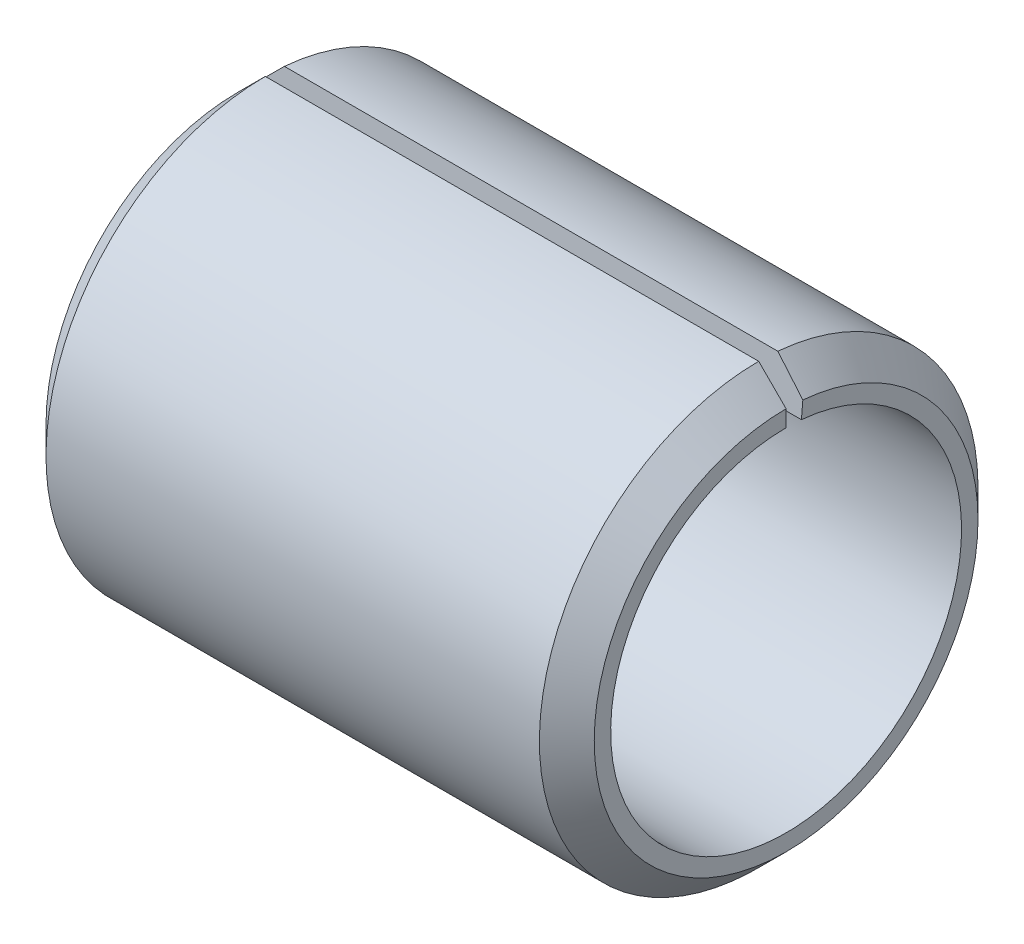
SolidWorks part; units mm, degrees
material "AISI 1020 Acier laminé à froid"
ref_plane "Plan de face" through (0, 0, 0) normal (0, 0, 1) x (1, 0, 0)
ref_plane "Plan de dessus" through (0, 0, 0) normal (0, 1, 0) x (1, 0, 0)
ref_plane "Plan de droite" through (0, 0, 0) normal (1, 0, 0) x (0, 0, -1)
sketch "Esquisse1" plane through (0, 0, 0) normal (0, 0, 1) x (1, 0, 0)
  line L0 (-5, 3.2) -> (-5, 4)
  line L1 (-5, 4) -> (5, 4)
  line L2 (5, 4) -> (5, 3.2)
  line L3 (-5, 3.2) -> (5, 3.2)
  line L4 (-7.5313, 0) -> (11.182, 0) construction
  dimension "D1" = 4
  dimension "D2" = 3.2
  dimension "D3" = 10
  dimension "D4" = 5
revolve "Révolution1" add sketch "Esquisse1" angle 355 about L4
chamfer "Chanfrein1" distance 0.5 angle 45 2 edges at (-5, -3.9962, 0.1745) (5, -3.9962, 0.1745)
